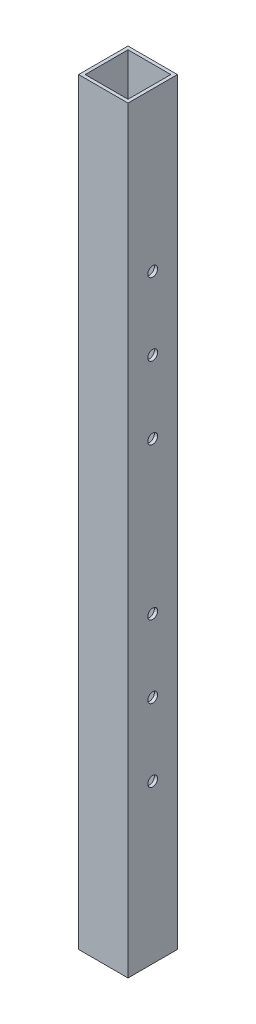
SolidWorks part; units mm, degrees
material "6061-O (SS)"
ref_plane "前视基准面" through (0, 0, 0) normal (0, 0, 1) x (1, 0, 0)
ref_plane "上视基准面" through (0, 0, 0) normal (0, 1, 0) x (1, 0, 0)
ref_plane "右视基准面" through (0, 0, 0) normal (1, 0, 0) x (0, 0, -1)
sketch "草图1" plane through (0, 0, 0) normal (0, 1, 0) x (1, 0, 0)
  line B0 (-6.5, 6.5) -> (6.5, 6.5)
  line B1 (-7.5, -7.5) -> (7.5, -7.5)
  line B2 (-7.5, -7.5) -> (-7.5, 7.5)
  line B3 (-7.5, 7.5) -> (7.5, 7.5)
  line B4 (7.5, -7.5) -> (7.5, 7.5)
  line B5 (6.5, -6.5) -> (6.5, 6.5)
  line B6 (-6.5, -6.5) -> (6.5, -6.5)
  line B7 (-6.5, -6.5) -> (-6.5, 6.5)
sketch_block_instance "块-15X15X1-1"
sketch_block "块-15X15X1" parameters "D1"=15
extrude "凸台-拉伸1" add sketch "草图1" along normal blind 230
sketch "草图2" plane through (7.5, 0, 0) normal (1, 0, 0) x (0, 0, -1)
  line L0 (-7.5, 115) -> (7.5, 115) construction
  line L1 (-7.5, 230) -> (-7.5, 0) construction
  line L2 (7.5, 230) -> (7.5, 0) construction
  line L3 (0, 160) -> (0, 70) construction
  circle A0 centre (0, 160) radius 1.5
  circle A1 centre (0, 138) radius 1.5
  circle A2 centre (0, 182) radius 1.5
  circle A3 centre (0, 48) radius 1.5
  circle A4 centre (0, 92) radius 1.5
  circle A5 centre (0, 70) radius 1.5
  point P13 (0, 0)
  point P15 (0, 115)
  dimension "D2" = 3
  dimension "D3" = 22
  dimension "D4" = 22
  dimension "D1" = 45
extrude "切除-拉伸1" cut sketch "草图2" against normal through all
